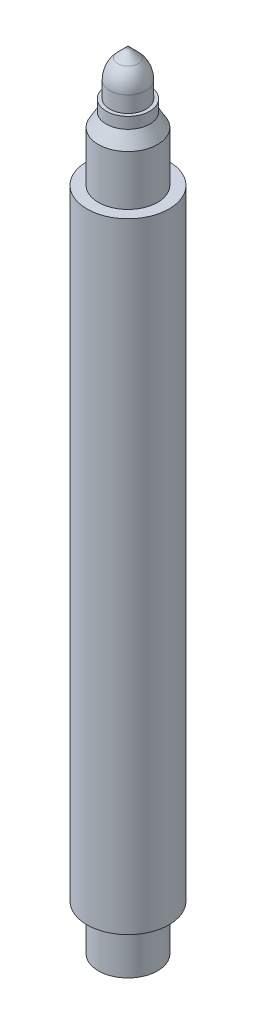
SolidWorks part; units mm, degrees
ref_plane "Front Plane" through (0, 0, 0) normal (0, 0, 1) x (1, 0, 0)
ref_plane "Top Plane" through (0, 0, 0) normal (0, 1, 0) x (1, 0, 0)
ref_plane "Right Plane" through (0, 0, 0) normal (1, 0, 0) x (0, 0, -1)
sketch "Sketch1" plane through (0, 0, 0) normal (0, 0, 1) x (1, 0, 0)
  line L0 (0, 43.5248) -> (0, -63.6126) construction
  line L1 (-4.5, 34) -> (0, 34)
  line L2 (-4.5, 34) -> (-4.5, -34)
  line L3 (-4.5, -34) -> (0, -34)
  line L5 (-4.5, 34) -> (0, 0) construction
  line L6 (-4.5, -34) -> (0, 0) construction
  line L7 (0, 34) -> (0, -34)
  point P0 (0, 0)
  dimension "D1" = 68
  dimension "D2" = 4.5
  dimension "D3" = 34
revolve "Revolve1" add sketch "Sketch1" angle 360 about L0
sketch "Sketch2" plane through (0, -34, 0) normal (0, -1, 0) x (1, 0, 0)
  circle A0 centre (0, 0) radius 3.25
  dimension "D1" = 6.5
extrude "Boss-Extrude1" add sketch "Sketch2" along normal blind 5
sketch "Sketch3" plane through (0, 34, 0) normal (0, 1, 0) x (1, 0, 0)
  circle A0 centre (0, 0) radius 3.25
  dimension "D1" = 6.5
extrude "Boss-Extrude2" add sketch "Sketch3" along normal blind 7
chamfer "Chamfer1" distance 1.5 angle 30 1 edges at (0, 41, 3.25)
sketch "Sketch4" plane through (0, 41, 0) normal (0, 1, 0) x (1, 0, 0)
  circle A0 centre (0, 0) radius 2.384
extrude "Boss-Extrude3" add sketch "Sketch4" along normal blind 1.23
sketch "Sketch5" plane through (0, 0, 0) normal (1, 0, 0) x (0, 0, -1)
  line L0 (0, 53.1544) -> (0, 42.4868) construction
  line L1 (0, 47.23) -> (-2, 45.23)
  line L2 (-2, 45.23) -> (-2, 42.23)
  line L3 (2.384, 42.23) -> (-2.384, 42.23) construction
  line L4 (-2, 42.23) -> (0, 42.23)
  line L5 (0, 42.23) -> (0, 47.23)
  dimension "D1" = 5
  dimension "D2" = 2
  dimension "D3" = 135
revolve "Revolve2" add sketch "Sketch5" angle 360 about L0
fillet "Fillet1" radius 3 1 edges at (0, 45.23, 2)
move or copy body "Body-Move/Copy1" bodies to move or copy 112 copy no translate (0, -47.23, 0)
ref_point "Pen-TIP"
